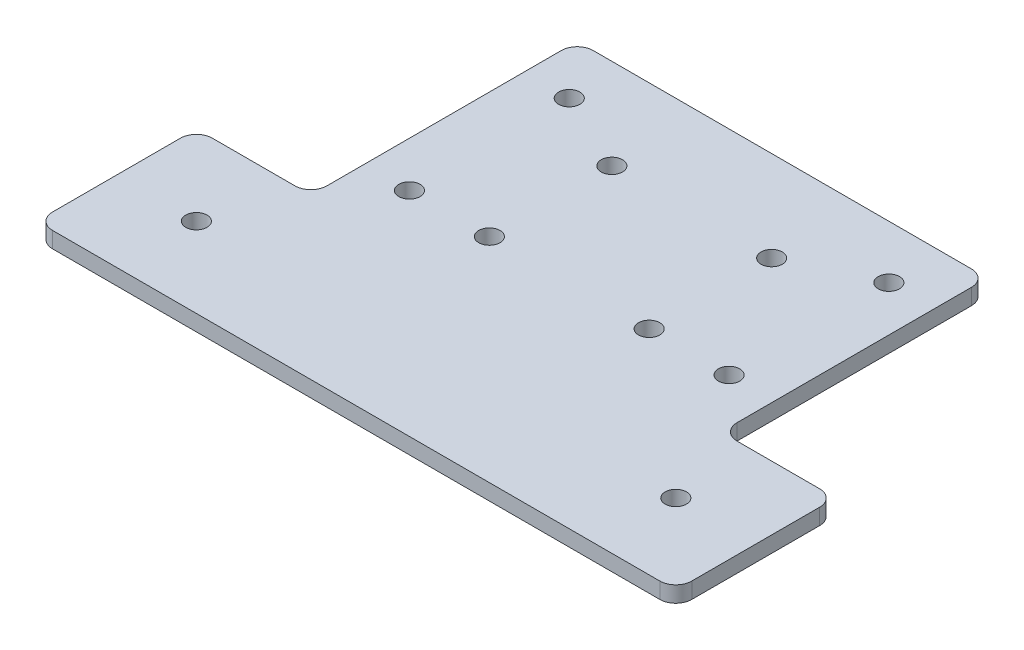
SolidWorks part; units mm, degrees
ref_plane "Płaszczyzna przednia" through (0, 0, 0) normal (0, 0, 1) x (1, 0, 0)
ref_plane "Płaszczyzna górna" through (0, 0, 0) normal (0, 1, 0) x (1, 0, 0)
ref_plane "Płaszczyzna prawa" through (0, 0, 0) normal (1, 0, 0) x (0, 0, -1)
sketch "Szkic1" plane through (0, 0, 0) normal (0, 1, 0) x (1, 0, 0)
  line L1 (-38.5, -40) -> (38.5, -40)
  line L2 (-38.5, -40) -> (-38.5, 40)
  line L3 (-38.5, 40) -> (38.5, 40)
  line L4 (38.5, -40) -> (38.5, 40)
  line L5 (-38.5, -40) -> (38.5, 40) construction
  line L6 (-38.5, 40) -> (38.5, -40) construction
  point P0 (0, 0)
  dimension "D1" = 77
  dimension "D2" = 80
extrude "Dodanie-wyciągnięcie1" add sketch "Szkic1" along normal blind 3
sketch "Szkic2" plane through (0, 3, 0) normal (0, 1, 0) x (1, 0, 0)
  line L2 (-38.5, 40) -> (-38.5, -40) construction
  line L3 (38.5, -40) -> (38.5, 40) construction
  line L6 (38.5, 40) -> (-38.5, 40) construction
  circle A0 centre (-23.5, -25) radius 2.5
  circle A1 centre (23.5, -25) radius 2.5
  circle A2 centre (-30, 30) radius 2
  circle A3 centre (-30, 0) radius 2
  circle A4 centre (30, 0) radius 2
  circle A5 centre (30, 30) radius 2
  point P0 (-38.5, 0)
  dimension "D2" = 5
  dimension "D7" = 10
  dimension "D11" = 4
  dimension "D12" = 4
  dimension "D13" = 4
  dimension "D14" = 4
  dimension "D3" = 15
  dimension "D4" = 15
  dimension "D5" = 8.5
  dimension "D6" = 8.5
  dimension "D8" = 10
  dimension "D9" = 40
  dimension "D10" = 40
  dimension "D15" = 8.5
  dimension "D16" = 8.5
extrude "Wytnij-wyciągnięcie1" cut sketch "Szkic2" against normal up to next
fillet "Zaokrąglenie1" radius 3 1 edges at (-38.5, 1.5, -40)
fillet "Zaokrąglenie2" radius 3 3 edges at (-38.5, 1.5, 40) (38.5, 1.5, 40) (38.5, 1.5, -40)
sketch "Szkic3" plane through (0, 0, 0) normal (0, 1, 0) x (1, 0, 0)
  circle A0 centre (-15, 23) radius 2
  circle A1 centre (15, 23) radius 2
  circle A2 centre (-15, 0) radius 2
  circle A3 centre (15, 0) radius 2
extrude "Wytnij-wyciągnięcie3" cut sketch "Szkic3" along normal up to next
sketch "Szkic5" plane through (0, 3, 0) normal (0, 1, 0) x (1, 0, 0)
  line L1 (-60, -40) -> (60, -40)
  line L2 (-60, -40) -> (-60, -10)
  line L3 (-60, -10) -> (60, -10)
  line L4 (60, -40) -> (60, -10)
  point P4 (0, 0)
  point P5 (0, 0)
  point P6 (0, 0)
extrude "Dodanie-wyciągnięcie2" add sketch "Szkic5" against normal blind 3
fillet "Zaokrąglenie4" radius 3 6 edges at (38.5, 1.5, 10) (60, 1.5, 10) (60, 1.5, 40) (-60, 1.5, 40) (-60, 1.5, 10) (-38.5, 1.5, 10)
sketch "Szkic6" plane through (0, 3, 0) normal (0, 1, 0) x (1, 0, 0)
  circle A0 centre (-45, -25) radius 2
  circle A1 centre (45, -25) radius 2
extrude "Wytnij-wyciągnięcie4" cut sketch "Szkic6" against normal up to next
